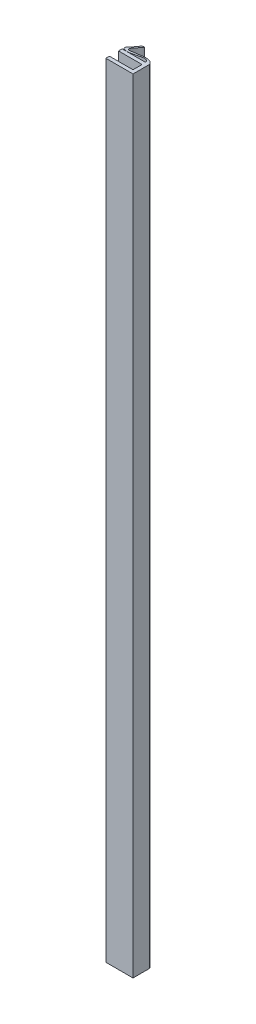
SolidWorks part; units mm, degrees
ref_plane "Front Plane" through (0, 0, 0) normal (0, 0, 1) x (1, 0, 0)
ref_plane "Top Plane" through (0, 0, 0) normal (0, 1, 0) x (1, 0, 0)
ref_plane "Right Plane" through (0, 0, 0) normal (1, 0, 0) x (0, 0, -1)
sketch "Sketch2" plane through (0, 0, 0) normal (0, 0, 1) x (1, 0, 0)
  line L1 (-138.3333, 81.4583) -> (-123.3333, 81.4583)
  line L2 (-138.3333, 81.4583) -> (-138.3333, -350.5417)
  line L3 (-138.3333, -350.5417) -> (-123.3333, -350.5417)
  line L4 (-123.3333, 81.4583) -> (-123.3333, -350.5417)
  dimension "D1" = 15
  dimension "D2" = 432
extrude "Boss-Extrude1" add sketch "Sketch2" along normal blind 9
sketch "Sketch3" plane through (-138.3333, 0, 0) normal (-1, 0, 0) x (0, 0, 1)
  line L0 (0, 81.4583) -> (0, -350.5417) construction
  line L1 (2, 81.4583) -> (7, 81.4583)
  line L2 (2, 81.4583) -> (2, -350.5417)
  line L3 (2, -350.5417) -> (7, -350.5417)
  line L4 (7, 81.4583) -> (7, -350.5417)
  line L5 (9, 81.4583) -> (9, -350.5417) construction
  line L6 (9, 81.4583) -> (0, 81.4583) construction
  line L7 (9, -350.5417) -> (0, -350.5417) construction
  dimension "D1" = 2
  dimension "D2" = 2
  dimension "D3" = 0
  dimension "D4" = 0
extrude "Cut-Extrude1" cut sketch "Sketch3" against normal blind 13
sketch "Sketch4" plane through (0, -350.5417, 0) normal (0, -1, 0) x (-1, 0, 0)
  line L0 (134.6279, 5.826) -> (137.5197, 2.6507)
  line L1 (138.3333, 0) -> (123.3333, 0) construction
  line L2 (123.3333, 0) -> (125.5367, 0)
  spline S0 degree 3 poles (123.3333, 0) (125.0205, 5.1351) (139.7925, -2.0163) (135.1203, 4.3763) (131.8386, 7.6064) (135.2338, 6.5326) (134.6279, 5.826) knots 0 0 0 0 0.624715 0.82543 0.905763 1 1 1 1
  spline S1 degree 3 poles (137.5197, 2.6507) (139.0656, 0.9201) (135.49, -0.5805) (131.4289, 1.1508) (125.5696, 2.1398) (125.5367, 0) knots 0 0 0 0 0.203698 0.642664 1 1 1 1
  point P6 (125.5556, 1.3844)
  point P10 (0, 0)
  point P13 (131.8306, 1.5167)
  point P16 (131.3959, 1.5545)
  point P18 (133.4561, 1.6301)
  point P19 (125.5367, 0)
  point P22 (134.5712, 3.539)
  point P23 (134.4956, 3.539)
  point P24 (136.896, 0.2314)
  point P25 (137.8032, 0.5338)
  point P26 (137.5197, 2.6507)
  point P27 (133.0024, 6.9412)
  point P28 (133.5884, 6.9223)
  point P29 (134.6279, 5.826)
  point P30 (136.4802, 1.7435)
  point P31 (133.9853, 5.448)
  point P32 (0, 0)
extrude "Boss-Extrude2" add sketch "Sketch4" against normal up to surface (432 mm away) up to face at (-131.3333, 81.4583, 4.5)
